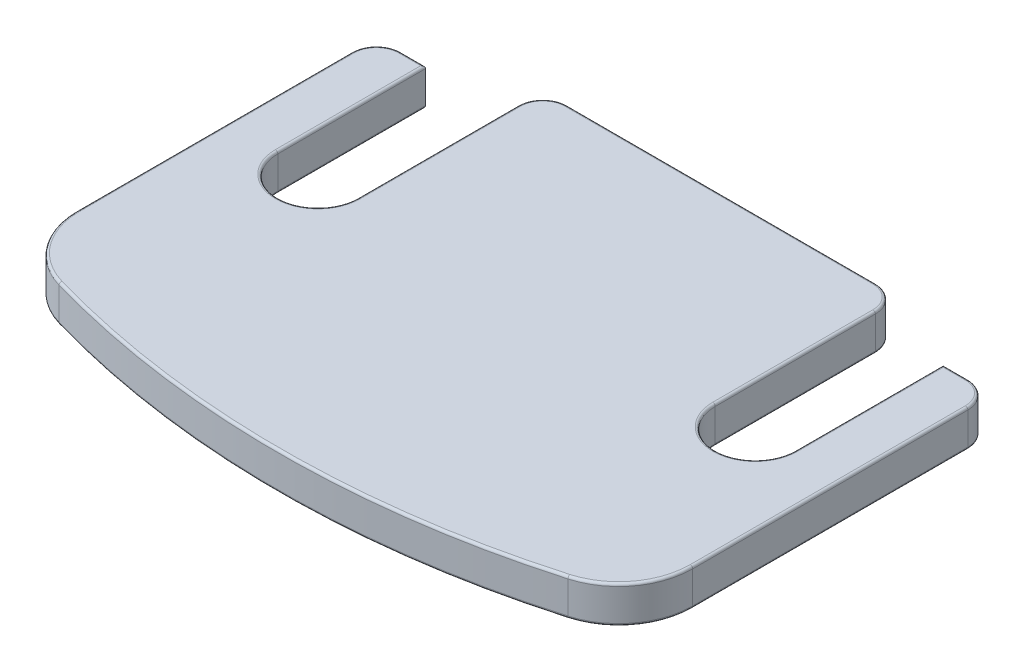
SolidWorks part; units mm, degrees
ref_plane "Front Plane" through (0, 0, 0) normal (0, 0, 1) x (1, 0, 0)
ref_plane "Top Plane" through (0, 0, 0) normal (0, 1, 0) x (1, 0, 0)
ref_plane "Right Plane" through (0, 0, 0) normal (1, 0, 0) x (0, 0, -1)
sketch "Sketch1" plane through (0, 0, 0) normal (0, 1, 0) x (1, 0, 0)
  line L1 (-25, 8.6675) -> (-25, 31)
  line L2 (-23, 33) -> (-21, 33)
  line L3 (-21, 33) -> (-21, 21)
  line L5 (-14.5, 21) -> (-14.5, 34)
  line L6 (-12.5, 36) -> (12.5, 36)
  line L7 (0, 0) -> (0, 36) construction
  line L8 (25, 8.6675) -> (25, 31)
  line L9 (23, 33) -> (21, 33)
  line L10 (21, 33) -> (21, 21)
  line L12 (14.5, 21) -> (14.5, 34)
  line L13 (0, -55) -> (0, 55) construction
  arc A0 (-20.6522, 2.8995) -> (20.6522, 2.8995) centre (0, 75) ccw
  arc A1 (-21, 21) -> (-14.5, 21) centre (-17.75, 21) ccw
  arc A2 (14.5, 21) -> (21, 21) centre (17.75, 21) ccw
  arc A3 (20.6522, 2.8995) -> (25, 8.6675) centre (19, 8.6675) ccw
  arc A4 (-20.6522, 2.8995) -> (-25, 8.6675) centre (-19, 8.6675) cw
  arc A5 (14.5, 34) -> (12.5, 36) centre (12.5, 34) ccw
  arc A6 (-14.5, 34) -> (-12.5, 36) centre (-12.5, 34) cw
  arc A7 (25, 31) -> (23, 33) centre (23, 31) ccw
  arc A8 (-25, 31) -> (-23, 33) centre (-23, 31) cw
  point P16 (-93.6061, 22.3883)
  point P27 (14.5, 36)
  point P30 (-14.5, 36)
  point P33 (25, 33)
  point P36 (-25, 33)
  point P37 (-94.8738, 50.1719)
  dimension "D8" = 150
  dimension "D3" = 3.25
  dimension "D6" = 3.25
  dimension "D10" = 6
  dimension "D11" = 2
  dimension "D1" = 33
  dimension "D2" = 36
  dimension "D4" = 21
  dimension "D5" = 4
  dimension "D7" = 25
extrude "Boss-Extrude1" add sketch "Sketch1" along normal blind 3
fillet "Fillet1" radius 0.2 36 edges at (-22, 0, -33) (-24.4142, 0, -32.4142) (-25, 0, -19.8338) (-23.7913, 0, -5.0559) (0, 0, 0) (23.7913, 0, -5.0559) (25, 0, -19.8338) (24.4142, 0, -32.4142) (22, 0, -33) (21, 0, -27) (14.5, 0, -27.5) (13.9142, 0, -35.4142) (0, 0, -36) (-13.9142, 0, -35.4142) (-14.5, 0, -27.5) (-21, 0, -27) (-14.5, 3, -27.5) (-13.9142, 3, -35.4142) (0, 3, -36) (13.9142, 3, -35.4142) (14.5, 3, -27.5) (21, 3, -27) (22, 3, -33) (24.4142, 3, -32.4142) (25, 3, -19.8338) (23.7913, 3, -5.0559) (0, 3, 0) (-23.7913, 3, -5.0559) (-25, 3, -19.8338) (-24.4142, 3, -32.4142) (-22, 3, -33) (-21, 3, -27) (17.75, 0, -17.75) (-17.75, 0, -17.75) (17.75, 3, -17.75) (-17.75, 3, -17.75)
ref_plane "Plane1" through (0, 0, -21) normal (0, 0, 1) x (0, -1, 0)
